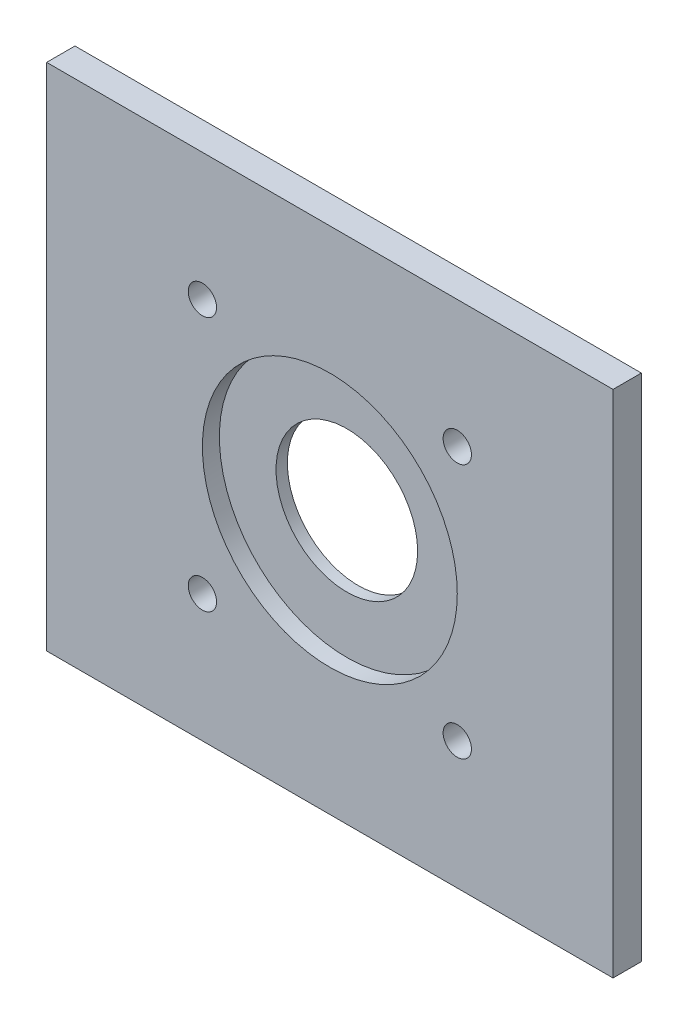
SolidWorks part; units mm, degrees
ref_plane "Front Plane" through (0, 0, 0) normal (0, 0, 1) x (1, 0, 0)
ref_plane "Top Plane" through (0, 0, 0) normal (0, 1, 0) x (1, 0, 0)
ref_plane "Right Plane" through (0, 0, 0) normal (1, 0, 0) x (0, 0, -1)
sketch "Sketch1" plane through (0, 0, 0) normal (0, 0, 1) x (1, 0, 0)
  line L13 (0, 0) -> (100, 0)
  line L14 (0, 0) -> (0, 90)
  line L15 (0, 90) -> (100, 90)
  line L16 (100, 0) -> (100, 90)
  line L17 (50, 90) -> (50, 0) construction
  line L19 (27.5, 67.5) -> (27.5, 22.5) construction
  line L20 (27.5, 22.5) -> (72.5, 22.5) construction
  line L21 (72.5, 22.5) -> (72.5, 67.5) construction
  line L22 (72.5, 67.5) -> (27.5, 67.5) construction
  line L23 (27.5, 22.5) -> (72.5, 67.5) construction
  line L25 (3, 45) -> (0, 45) construction
  circle A6 centre (27.5, 67.5) radius 2.5
  circle A7 centre (72.5, 67.5) radius 2.5
  circle A8 centre (72.5, 22.5) radius 2.5
  circle A9 centre (27.5, 22.5) radius 2.5
  circle A10 centre (50, 45) radius 12.5
  point P31 (50, 45)
  dimension "D5" = 5
  dimension "D9" = 25
  dimension "D1" = 90
  dimension "D2" = 100
  dimension "D6" = 45
  dimension "D7" = 45
extrude "Boss-Extrude1" add sketch "Sketch1" along normal blind 5
sketch "Sketch3" plane through (0, 0, 5) normal (0, 0, 1) x (1, 0, 0)
  circle A0 centre (50, 45) radius 15 construction
  circle A1 centre (50, 45) radius 12.5 construction
  circle A2 centre (50, 45) radius 22.5
  dimension "D1" = 7.5
  dimension "D2" = 30
extrude "Cut-Extrude2" cut sketch "Sketch3" against normal blind 3
